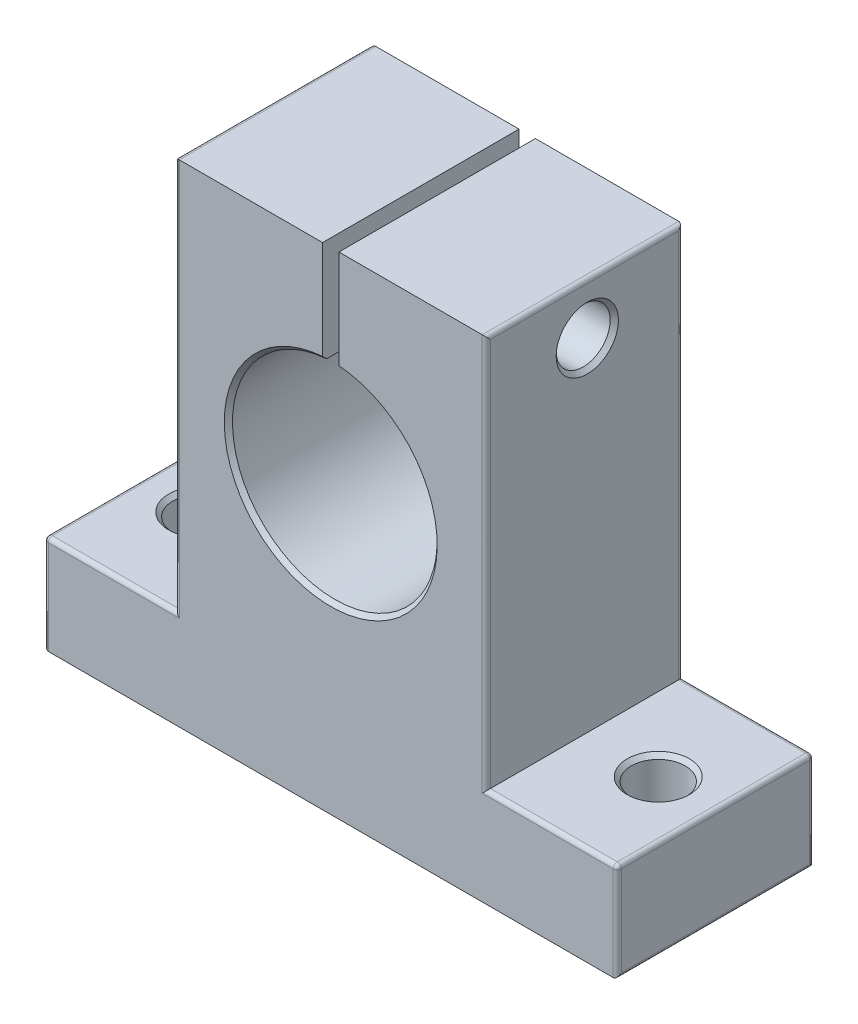
SolidWorks part; units mm, degrees
material "1060 Alloy"
ref_plane "Front Plane" through (0, 0, 0) normal (0, 0, 1) x (1, 0, 0)
ref_plane "Top Plane" through (0, 0, 0) normal (0, 1, 0) x (1, 0, 0)
ref_plane "Right Plane" through (0, 0, 0) normal (1, 0, 0) x (0, 0, -1)
sketch "Sketch1" plane through (0, 0, 0) normal (0, 0, 1) x (1, 0, 0)
  line L0 (0, 0) -> (-50000, 0) construction
  line L1 (0, 0) -> (0, 50000) construction
  line L2 (-35, -6) -> (-35, 6)
  line L3 (-35, 6) -> (-19, 6)
  line L4 (-19, 6) -> (-19, 54)
  line L5 (-19, 54) -> (-1, 54)
  line L6 (19, 54) -> (19, 6)
  line L7 (19, 6) -> (35, 6)
  line L8 (35, 6) -> (35, -6)
  line L9 (35, -6) -> (-35, -6)
  line L10 (28, -3) -> (28, 3) construction
  line L11 (-28, -3) -> (-28, 3) construction
  line L12 (-1, 54) -> (-1, 41.4599)
  line L13 (1, 54) -> (1, 41.4599)
  line L14 (1, 54) -> (19, 54)
  arc A0 (-1, 41.4599) -> (1, 41.4599) centre (0, 29) ccw
  point P8 (-35, 0)
  point P15 (0, -6)
  point P21 (28, 0)
  dimension "Shaft Diameter" = 25
  dimension "W" = 70
  dimension "P" = 38
  dimension "F" = 60
  dimension "G" = 12
  dimension "B" = 56
  dimension "D1" = 2
  dimension "h" = 35
extrude "Boss-Extrude1" add sketch "Sketch1" along normal mid plane 24
sketch "Sketch2" plane through (0, 6, 0) normal (0, 1, 0) x (1, 0, 0)
  line L0 (0, 0) -> (50000, 0) construction
  line L1 (0.3141, 0) -> (-49999.6859, 0) construction
  line L2 (0, 2.4842) -> (0, 50002.4842) construction
  circle A0 centre (28, 0) radius 3.3
  circle A1 centre (-28, 0) radius 3.3
  dimension "B" = 56
  dimension "S" = 6.6
extrude "Cut-Extrude1" cut sketch "Sketch2" against normal through all
sketch "Sketch5" plane through (-1, 0, 0) normal (1, 0, 0) x (0, 0, -1)
  line L0 (-12, 47.73) -> (12, 47.73) construction
  line L1 (12, 41.4599) -> (12, 54) construction
  line L2 (0, 54) -> (0, 41.4599) construction
  line L3 (-12, 54) -> (12, 54) construction
  line L4 (-12, 41.4599) -> (12, 41.4599) construction
  line L5 (-12, 41.4599) -> (-12, 54) construction
  circle A0 centre (0.3307, 47.73) radius 3.3
  dimension "Clamping bold" = 6.6
extrude "Cut-Extrude2" cut sketch "Sketch5" against normal through all both and the other way through all
chamfer "Chamfer2" distance 0.5 angle 45 6 edges at (0, 16.5, -12) (0, 16.5, 12) (-19, 47.73, -3.6307) (-24.7, 6, 0) (19, 47.73, 2.9693) (24.7, 6, 0)
fillet "Fillet2" radius 0.5 18 edges at (35, -6, 0) (35, 0, 12) (35, 6, 0) (35, 0, -12) (-35, 6, 0) (-35, 0, 12) (-35, -6, 0) (-35, 0, -12) (-27, 6, -12) (-27, 6, 12) (-19, 30, 12) (-19, 54, 0) (-19, 30, -12) (19, 30, -12) (19, 30, 12) (27, 6, 12) (27, 6, -12) (19, 54, 0)
equation "\"W\"= \"W@Sketch1\"'Width"
equation "\"B\"= \"B@Sketch1\"'between hold"
equation "\"F\"= \"F@Sketch1\"'Hight"
equation "\"P\"= \"P@Sketch1\""
equation "\"G\"= \"G@Sketch1\""
equation "\"Shaft diameter\"= \"Shaft Diameter@Sketch1\""
equation "\"S\"= \"S@Sketch2\"'M6"
equation "\"Clamping bold\"= 6.6'M6"
equation "\"h\"= \"h@Sketch1\""
